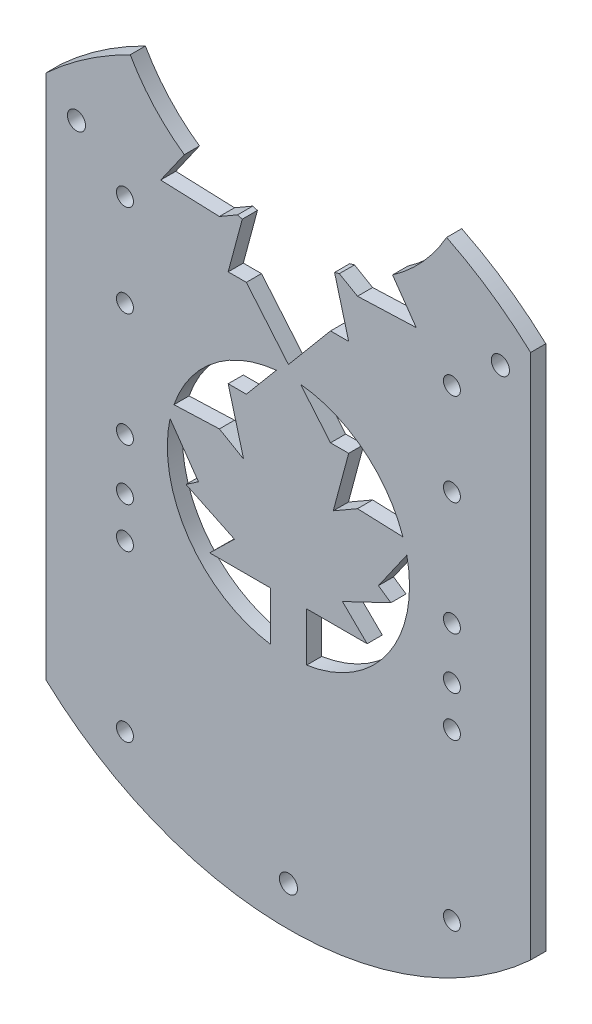
SolidWorks part; units mm, degrees
ref_plane "Front Plane" through (0, 0, 0) normal (0, 0, 1) x (1, 0, 0)
ref_plane "Top Plane" through (0, 0, 0) normal (0, 1, 0) x (1, 0, 0)
ref_plane "Right Plane" through (0, 0, 0) normal (1, 0, 0) x (0, 0, -1)
sketch "Sketch1" plane through (0, 0, 0) normal (0, 0, 1) x (1, 0, 0)
  line L0 (0, 47.9049) -> (0, -75) construction
  line L1 (-50.8, 55.1757) -> (-50.8, -55.1757)
  line L2 (50.8, 55.1757) -> (50.8, -55.1757)
  arc A0 (-33.1727, 67.265) -> (-50.8, 55.1757) centre (0, 0) ccw
  arc A1 (-33.1727, 67.265) -> (33.1727, 67.265) centre (0, 86.0049) ccw
  circle A2 centre (0, -66.675) radius 1.8987
  circle A3 centre (-44.45, 49.6966) radius 1.8987
  circle A4 centre (44.45, 49.6966) radius 1.8986
  arc A5 (-50.8, -55.1757) -> (50.8, -55.1757) centre (0, 0) ccw
  arc A6 (50.8, 55.1757) -> (33.1727, 67.265) centre (0, 0) ccw
  circle A7 centre (0, 0) radius 66.675 construction
  dimension "D8" = 3.7973
  dimension "D11" = 3.7973
  dimension "D5" = 150
  dimension "D7" = 133.35
  dimension "D2" = 66.3453
  dimension "D3" = 38.1
  dimension "D4" = 44.45
  dimension "D6" = 50.8
extrude "Boss-Extrude3" add sketch "Sketch1" along normal blind 3.175
sketch "Sketch3" plane through (0, 0, 3.175) normal (0, 0, 1) x (1, 0, 0)
  line L0 (0, 47.9049) -> (0, -75) construction
  line L1 (0, 25.4) -> (0, -25.4) construction
  line L2 (8.8271, 17.78) -> (2.54, 25.2727)
  line L3 (8.8271, 17.78) -> (12.6371, 17.78)
  line L4 (12.6371, 17.78) -> (9.4043, 5.715)
  line L5 (9.4043, 5.715) -> (14.4843, 8.6479)
  line L6 (14.4843, 8.6479) -> (24.0093, 8.2894)
  line L7 (18.8681, -3.1406) -> (24.8262, 5.3684)
  line L8 (18.8681, -3.1406) -> (21.4871, -4.9356)
  line L9 (21.4871, -4.9356) -> (11.3271, -9.7979)
  line L10 (11.3271, -9.7979) -> (16.51, -14.8779)
  line L11 (16.51, -14.8779) -> (3.81, -14.8779)
  line L12 (3.81, -14.8779) -> (3.81, -25.1126)
  line L13 (-3.81, -14.8779) -> (-3.81, -25.1126)
  line L14 (-16.51, -14.8779) -> (-3.81, -14.8779)
  line L15 (-11.3271, -9.7979) -> (-16.51, -14.8779)
  line L16 (-21.4871, -4.9356) -> (-11.3271, -9.7979)
  line L17 (-18.8681, -3.1406) -> (-21.4871, -4.9356)
  line L18 (-18.8681, -3.1406) -> (-24.8262, 5.3684)
  line L19 (-14.4843, 8.6479) -> (-24.0093, 8.2894)
  line L20 (-9.4043, 5.715) -> (-14.4843, 8.6479)
  line L21 (-12.6371, 17.78) -> (-9.4043, 5.715)
  line L22 (-8.8271, 17.78) -> (-12.6371, 17.78)
  line L23 (-8.8271, 17.78) -> (-2.54, 25.2727)
  arc A0 (-33.1727, 67.265) -> (33.1727, 67.265) centre (0, 86.0049) ccw construction
  arc A1 (-50.8, -55.1757) -> (50.8, -55.1757) centre (0, 0) ccw construction
  arc A2 (3.81, -25.1126) -> (24.8262, 5.3684) centre (0, 0) ccw
  arc A3 (-24.8262, 5.3684) -> (-3.81, -25.1126) centre (0, 0) ccw
  arc A4 (-2.54, 25.2727) -> (-24.0093, 8.2894) centre (0, 0) ccw
  arc A5 (24.0093, 8.2894) -> (2.54, 25.2727) centre (0, 0) ccw
  circle A6 centre (0, 0) radius 25.4 construction
  dimension "D1" = 7.62
  dimension "D2" = 3.81
  dimension "D3" = 12.065
  dimension "D4" = 75
  dimension "D5" = 5.08
  dimension "D6" = 45
  dimension "D7" = 9.525
  dimension "D8" = 3.175
  dimension "D9" = 10.16
  dimension "D10" = 60
  dimension "D11" = 5.08
  dimension "D12" = 12.7
  dimension "D13" = 70
  dimension "D14" = 3.81
  dimension "D15" = 2.921
  dimension "D16" = 35
  dimension "D17" = 40
extrude "Cut-Extrude2" cut sketch "Sketch3" against normal up to surface (3.175 mm away) up to face at (1.8987, -66.675, 0)
sketch "Sketch4" plane through (0, 0, 3.175) normal (0, 0, 1) x (1, 0, 0)
  line L0 (0, 47.9049) -> (0, -75) construction
  line L1 (-38.1, 44.7299) -> (38.1, 44.7299) construction
  line L2 (-38.1, 44.7299) -> (-38.1, -6.0701) construction
  line L3 (-38.1, -6.0701) -> (38.1, -6.0701) construction
  line L4 (38.1, 44.7299) -> (38.1, -6.0701) construction
  line L5 (0, 44.7299) -> (0, -6.0701) construction
  line L6 (-38.1, 19.3299) -> (38.1, 19.3299) construction
  line L7 (-38.1, -9.2451) -> (38.1, -9.2451) construction
  line L8 (-38.1, -9.2451) -> (-38.1, -60.0451) construction
  line L9 (-38.1, -60.0451) -> (38.1, -60.0451) construction
  line L10 (38.1, -9.2451) -> (38.1, -60.0451) construction
  line L11 (0, -9.2451) -> (0, -60.0451) construction
  line L12 (-38.1, -34.6451) -> (38.1, -34.6451) construction
  arc A0 (-33.1727, 67.265) -> (33.1727, 67.265) centre (0, 86.0049) ccw construction
  arc A1 (-50.8, -55.1757) -> (50.8, -55.1757) centre (0, 0) ccw construction
  circle A2 centre (-34.29, 40.9199) radius 1.778
  circle A3 centre (34.29, 40.9199) radius 1.778
  circle A4 centre (34.29, -2.2601) radius 1.778
  circle A5 centre (-34.29, -2.2601) radius 1.778
  circle A6 centre (-34.29, -13.0551) radius 1.778
  circle A7 centre (34.29, -13.0551) radius 1.778
  circle A8 centre (34.29, -56.2351) radius 1.778
  circle A9 centre (-34.29, -56.2351) radius 1.778
  dimension "D3" = 3.556
  dimension "D5" = 3.81
  dimension "D6" = 3.81
  dimension "D7" = 3.556
  dimension "D1" = 76.2
  dimension "D2" = 50.8
  dimension "D4" = 3.175
  dimension "D8" = 3.81
  dimension "D9" = 3.81
  dimension "D10" = 3.175
  dimension "D11" = 50.8
extrude "Cut-Extrude3" cut sketch "Sketch4" against normal up to surface (3.175 mm away) up to face at (-12.3976, 14.4374, 0)
sketch "Sketch5" plane through (0, 0, 3.175) normal (0, 0, 1) x (1, 0, 0)
  line L0 (-38.1, 25.4) -> (38.1, 25.4) construction
  line L1 (-38.1, 25.4) -> (-38.1, -25.4) construction
  line L2 (-38.1, -25.4) -> (38.1, -25.4) construction
  line L3 (38.1, 25.4) -> (38.1, -25.4) construction
  line L4 (0, 25.4) -> (0, -25.4) construction
  line L5 (-38.1, 0) -> (38.1, 0) construction
  line L6 (0, 47.9049) -> (0, -75) construction
  line L7 (-50.8, 0) -> (50.8, 0) construction
  line L8 (-50.8, 55.1757) -> (-50.8, -55.1757) construction
  line L9 (50.8, -55.1757) -> (50.8, 55.1757) construction
  circle A0 centre (-34.29, 21.59) radius 1.778
  circle A1 centre (34.29, 21.59) radius 1.778
  circle A2 centre (34.29, -21.59) radius 1.778
  circle A3 centre (-34.29, -21.59) radius 1.778
  arc A4 (-33.1727, 67.265) -> (33.1727, 67.265) centre (0, 86.0049) ccw construction
  arc A5 (-50.8, -55.1757) -> (50.8, -55.1757) centre (0, 0) ccw construction
  dimension "D1" = 3.556
  dimension "D2" = 3.81
  dimension "D3" = 3.81
  dimension "D4" = 76.2
  dimension "D5" = 50.8
extrude "Cut-Extrude4" cut sketch "Sketch5" against normal up to surface (3.175 mm away) up to face at (-32.512, -56.2351, 0)
sketch "Sketch6" plane through (0, 0, 3.175) normal (0, 0, 1) x (1, 0, 0)
  line L0 (0, 47.9049) -> (0, -75) construction
  line L1 (0, 30.48) -> (0, 81.28) construction
  line L2 (-8.8271, 38.1) -> (-2.54, 30.6073)
  line L3 (-8.8271, 38.1) -> (-12.6371, 38.1)
  line L4 (-12.6371, 38.1) -> (-9.4043, 50.165)
  line L5 (-9.4043, 50.165) -> (-14.4843, 47.2321)
  line L6 (-14.4843, 47.2321) -> (-24.0093, 47.5906)
  line L7 (-18.8681, 59.0206) -> (-24.8262, 50.5116)
  line L8 (-18.8681, 59.0206) -> (-21.4871, 60.8156) construction
  line L9 (-21.4871, 60.8156) -> (-11.3271, 65.6779) construction
  line L10 (-11.3271, 65.6779) -> (-16.51, 70.7579) construction
  line L11 (-16.51, 70.7579) -> (-3.81, 70.7579) construction
  line L12 (-3.81, 70.7579) -> (-3.81, 80.9926) construction
  line L13 (3.81, 70.7579) -> (3.81, 80.9926) construction
  line L14 (16.51, 70.7579) -> (3.81, 70.7579) construction
  line L15 (11.3271, 65.6779) -> (16.51, 70.7579) construction
  line L16 (21.4871, 60.8156) -> (11.3271, 65.6779) construction
  line L17 (18.8681, 59.0206) -> (21.4871, 60.8156) construction
  line L18 (18.8681, 59.0206) -> (24.8262, 50.5116)
  line L19 (14.4843, 47.2321) -> (24.0093, 47.5906)
  line L20 (9.4043, 50.165) -> (14.4843, 47.2321)
  line L21 (12.6371, 38.1) -> (9.4043, 50.165)
  line L22 (8.8271, 38.1) -> (12.6371, 38.1)
  line L23 (8.8271, 38.1) -> (2.54, 30.6073)
  line L24 (0, 27.5803) -> (-2.54, 30.6073)
  line L25 (0, 27.5803) -> (2.54, 30.6073)
  line L26 (24.8262, 50.5116) -> (26.798, 47.6956)
  line L27 (26.798, 47.6956) -> (24.0093, 47.5906)
  line L28 (-24.0093, 47.5906) -> (-26.798, 47.6956)
  line L29 (-26.798, 47.6956) -> (-24.8262, 50.5116)
  line L30 (-3.81, 80.9926) -> (3.81, 80.9926) construction
  line L31 (-25.2051, 59.0206) -> (25.2051, 59.0206) construction
  line L32 (-18.8681, 59.0206) -> (18.8681, 59.0206)
  arc A0 (-33.1727, 67.265) -> (33.1727, 67.265) centre (0, 86.0049) ccw construction
  arc A1 (-50.8, -55.1757) -> (50.8, -55.1757) centre (0, 0) ccw construction
  circle A6 centre (0, 55.88) radius 25.4 construction
  dimension "D19" = 55.88
  dimension "D18" = 50.8
  dimension "D1" = 7.62
  dimension "D2" = 3.81
  dimension "D3" = 12.065
  dimension "D4" = 75
  dimension "D5" = 5.08
  dimension "D6" = 45
  dimension "D7" = 9.525
  dimension "D8" = 3.175
  dimension "D9" = 10.16
  dimension "D10" = 60
  dimension "D11" = 5.08
  dimension "D12" = 12.7
  dimension "D13" = 70
  dimension "D14" = 3.81
  dimension "D15" = 2.921
  dimension "D16" = 35
  dimension "D17" = 40
  dimension "D20" = 2.7887
  dimension "D21" = 2.816
  dimension "D22" = 21.972
extrude "Cut-Extrude5" cut sketch "Sketch6" against normal up to surface (3.175 mm away) up to face at (-32.512, -21.59, 0)
